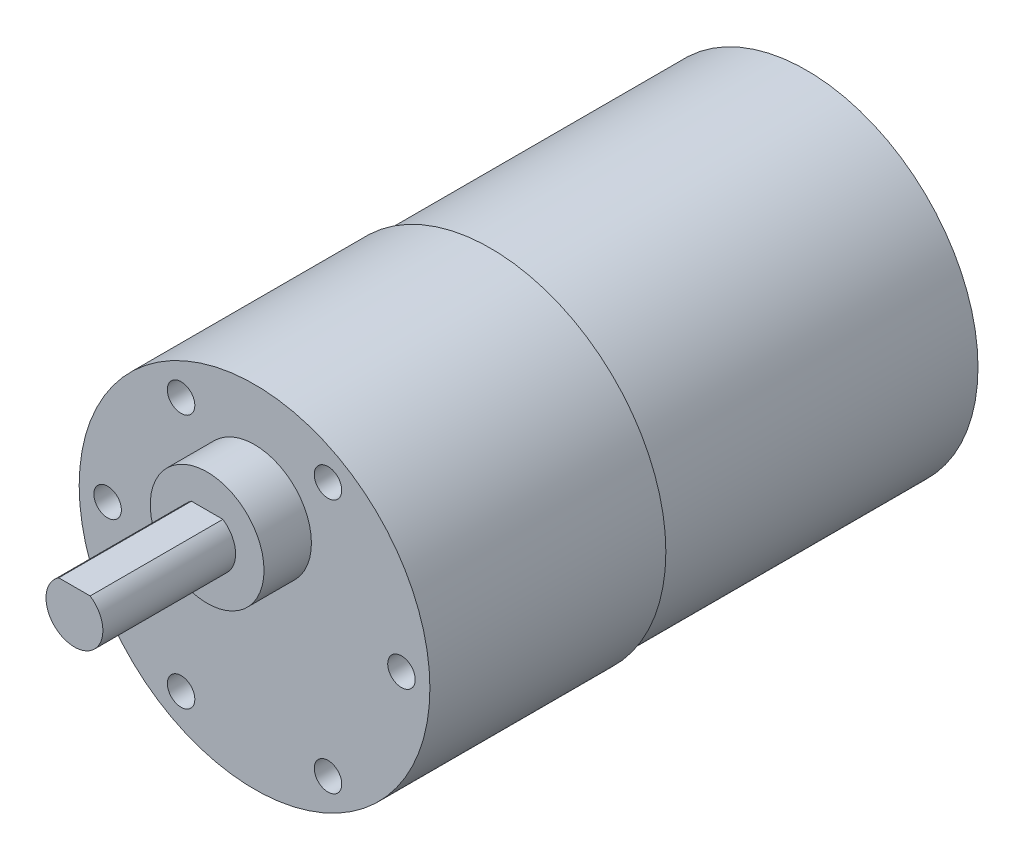
SolidWorks part; units mm, degrees
material "Alloy Steel (SS)"
ref_plane "Front Plane" through (0, 0, 0) normal (0, 0, 1) x (1, 0, 0)
ref_plane "Top Plane" through (0, 0, 0) normal (0, 1, 0) x (1, 0, 0)
ref_plane "Right Plane" through (0, 0, 0) normal (1, 0, 0) x (0, 0, -1)
sketch "Sketch1" plane through (0, 0, 0) normal (0, 0, 1) x (1, 0, 0)
  circle A0 centre (0, 0) radius 18.5
  dimension "D1" = 37
extrude "Boss-Extrude1" add sketch "Sketch1" along normal blind 24.892
sketch "Sketch2" plane through (0, 0, 0) normal (0, 0, -1) x (-1, 0, 0)
  circle A0 centre (0, 0) radius 18.1
  dimension "D1" = 36.2
extrude "Boss-Extrude2" add sketch "Sketch2" along normal blind 33.33
sketch "Sketch3" plane through (0, 0, 24.892) normal (0, 0, 1) x (1, 0, 0)
  circle A0 centre (0, 7) radius 6
  dimension "D1" = 12
  dimension "D2" = 7
extrude "Boss-Extrude3" add sketch "Sketch3" along normal blind 5
sketch "Sketch4" plane through (0, 0, 29.892) normal (0, 0, 1) x (1, 0, 0)
  line L0 (1.6583, 9.5) -> (-1.6583, 9.5)
  arc A0 (-1.6583, 9.5) -> (1.6583, 9.5) centre (0, 7) ccw
  dimension "D1" = 6
extrude "Boss-Extrude4" add sketch "Sketch4" along normal blind 14
sketch "Sketch5" plane through (0, 0, 24.892) normal (0, 0, 1) x (1, 0, 0)
  circle A0 centre (0, 0) radius 15.5 construction
  circle A1 centre (15.5, 0) radius 1.45
  circle A2 centre (7.75, -13.4234) radius 1.45
  circle A3 centre (-7.75, -13.4234) radius 1.45
  circle A4 centre (-15.5, 0) radius 1.45
  circle A5 centre (-7.75, 13.4234) radius 1.45
  circle A6 centre (7.75, 13.4234) radius 1.45
  point P18 (0, 0)
  dimension "D1" = 31
  dimension "D2" = 2.9
  dimension "D3" = 6
extrude "Cut-Extrude1" cut sketch "Sketch5" against normal blind 5
